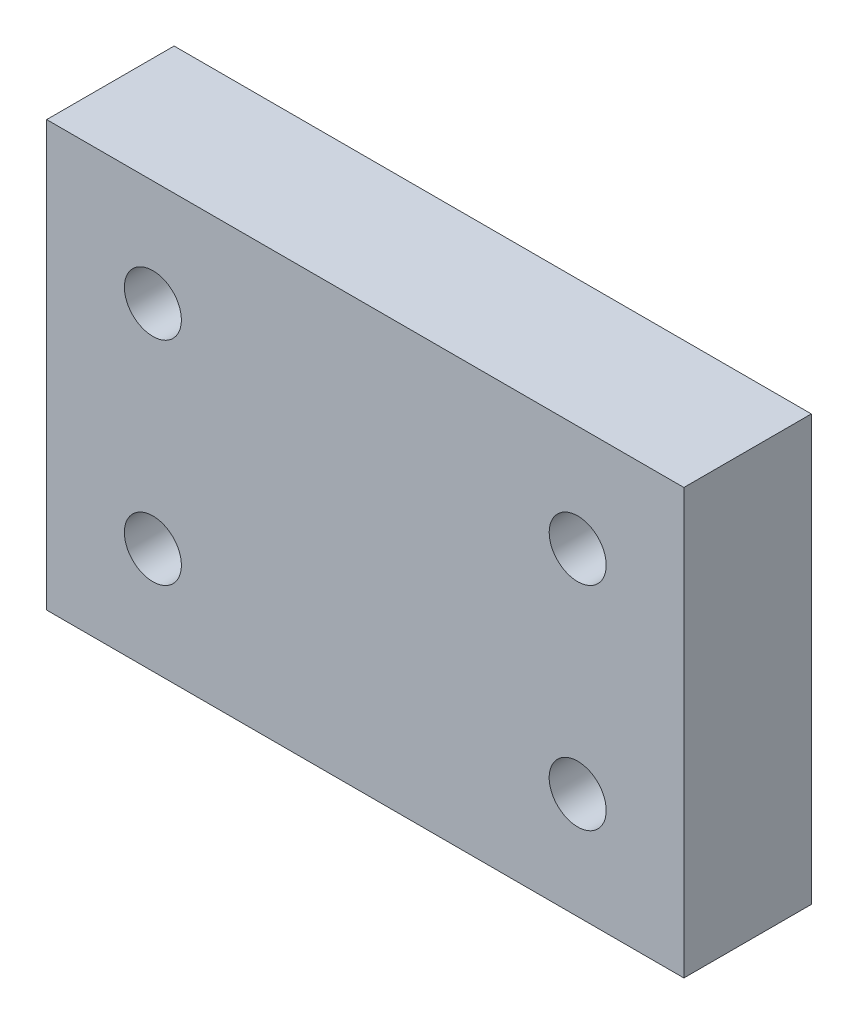
SolidWorks part; units mm, degrees
ref_plane "Plan de face" through (0, 0, 0) normal (0, 0, 1) x (1, 0, 0)
ref_plane "Plan de dessus" through (0, 0, 0) normal (0, 1, 0) x (1, 0, 0)
ref_plane "Plan de droite" through (0, 0, 0) normal (1, 0, 0) x (0, 0, -1)
sketch "Esquisse1" plane through (0, 0, 0) normal (0, 0, 1) x (1, 0, 0)
  line L0 (15, 20) -> (15, 0) construction
  line L1 (0, 0) -> (30, 0)
  line L2 (0, 0) -> (0, 20)
  line L3 (0, 20) -> (30, 20)
  line L4 (30, 0) -> (30, 20)
  line L5 (0, 10) -> (30, 10) construction
  circle A0 centre (5, 15) radius 1.3418
  circle A1 centre (25, 15) radius 1.3418
  circle A2 centre (25, 5) radius 1.3418
  circle A3 centre (5, 5) radius 1.3418
  dimension "D1" = 30
  dimension "D2" = 20
  dimension "D3" = 5
  dimension "D4" = 5
extrude "Boss.-Extru.1" add sketch "Esquisse1" along normal blind 6
